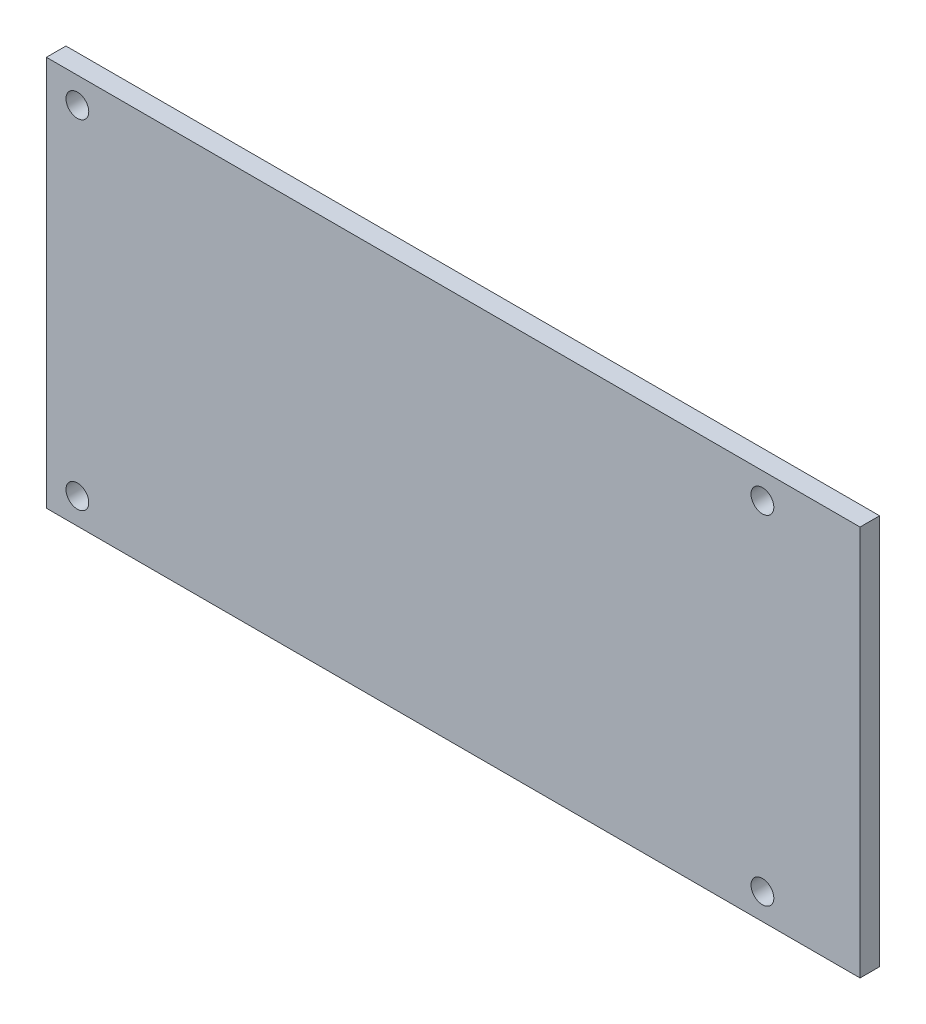
SolidWorks part; units mm, degrees
ref_plane "Спереди" through (0, 0, 0) normal (0, 0, 1) x (1, 0, 0)
ref_plane "Сверху" through (0, 0, 0) normal (0, 1, 0) x (1, 0, 0)
ref_plane "Справа" through (0, 0, 0) normal (1, 0, 0) x (0, 0, -1)
sketch "Эскиз1" plane through (0, 0, 0) normal (0, 0, 1) x (1, 0, 0)
  line L0 (-85.9081, 26) -> (80.9808, 26) construction
  line L1 (-62.5, 30) -> (62.5, 30)
  line L2 (-62.5, 30) -> (-62.5, -30)
  line L3 (-62.5, -30) -> (62.5, -30)
  line L4 (62.5, 30) -> (62.5, -30)
  line L5 (-62.5, 30) -> (62.5, -30) construction
  line L6 (-62.5, -30) -> (62.5, 30) construction
  line L7 (-62.5, 0) -> (62.5, 0) construction
  circle A0 centre (47.5, 26) radius 1.75
  circle A1 centre (-57.7426, 26) radius 1.75
  circle A2 centre (47.5, -26) radius 1.75
  circle A3 centre (-57.7426, -26) radius 1.75
  point P0 (0, 0)
  dimension "D2" = 3.5
  dimension "D1" = 4
  dimension "D3" = 26
  dimension "D4" = 15
  dimension "D5" = 125
extrude "Бобышка-Вытянуть1" add sketch "Эскиз1" along normal blind 3
